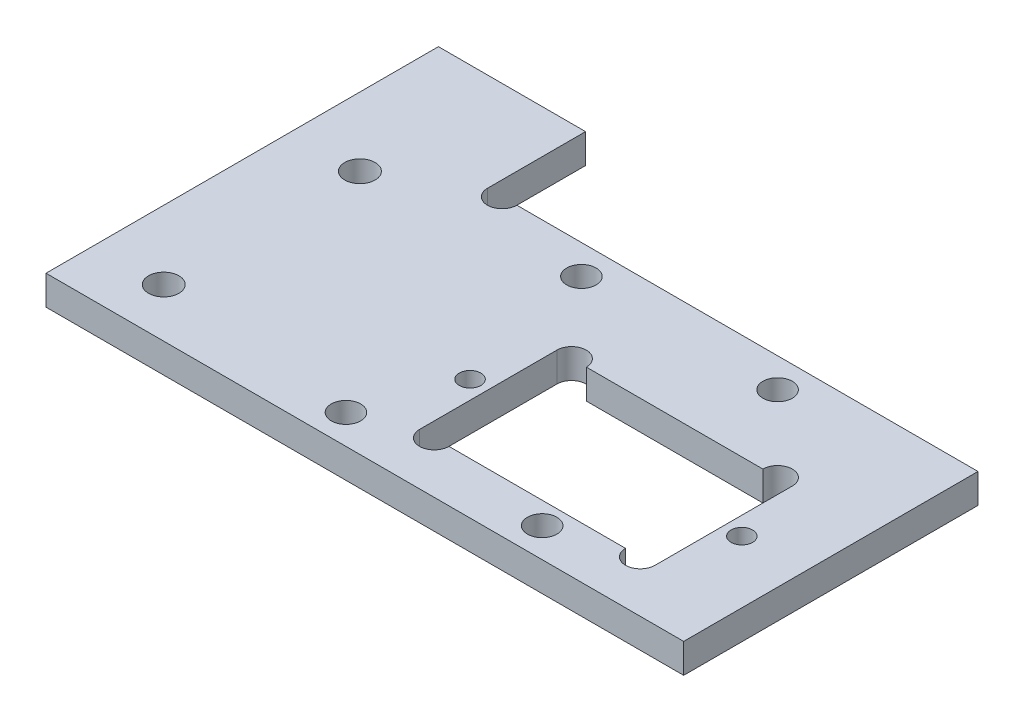
SolidWorks part; units mm, degrees
material "Thornel Mat VMA"
ref_plane "前视基准面" through (0, 0, 0) normal (0, 0, 1) x (1, 0, 0)
ref_plane "上视基准面" through (0, 0, 0) normal (0, 1, 0) x (1, 0, 0)
ref_plane "右视基准面" through (0, 0, 0) normal (1, 0, 0) x (0, 0, -1)
sketch "草图1" plane through (0, 0, 0) normal (0, 1, 0) x (1, 0, 0)
  line L0 (0, 20) -> (0, -20) construction
  line L1 (-32.5, 20) -> (32.5, 20)
  line L2 (-32.5, 20) -> (-32.5, -20)
  line L3 (-32.5, -20) -> (32.5, -20)
  line L4 (32.5, 20) -> (32.5, -20)
  line L5 (-32.5, 20) -> (32.5, -20) construction
  line L6 (-32.5, -20) -> (32.5, 20) construction
  point P0 (0, 0)
  dimension "D1" = 40
  dimension "D2" = 65
extrude "凸台-拉伸1" add sketch "草图1" along normal blind 3
ref_plane "基准面1" through (0, 0, 0) normal (0, -1, 0) x (-1, 0, 0)
ref_plane "基准面2" through (0, 0, 0) normal (0, -1, 0) x (-1, 0, 0)
sketch "草图2" plane through (0, 0, 0) normal (0, -1, 0) x (-1, 0, 0)
  line L0 (25.5, -20) -> (25.5, -15) construction
  line L1 (32.5, -20) -> (-32.5, -20) construction
  line L2 (25.5, -15) -> (25.5, 5) construction
  line L3 (32.5, 20) -> (32.5, -20) construction
  circle A0 centre (25.5, -15) radius 1.55
  circle A1 centre (25.5, 5) radius 1.55
  dimension "D1" = 3.1
  dimension "D2" = 3.1
  dimension "D3" = 7
  dimension "D4" = 5
  dimension "D5" = 20
extrude "切除-拉伸1" cut sketch "草图2" against normal blind 10
sketch "草图3" plane through (0, 0, 0) normal (0, -1, 0) x (-1, 0, 0)
  line L1 (-32.5, 20) -> (17.5, 20)
  line L2 (-32.5, 20) -> (-32.5, 10)
  line L3 (-32.5, 10) -> (17.5, 10)
  line L4 (17.5, 20) -> (17.5, 10)
  dimension "D1" = 10
  dimension "D2" = 50
extrude "切除-拉伸2" cut sketch "草图3" against normal blind 10
ref_plane "基准面3" through (0, 0, 0) normal (0, -1, 0) x (-1, 0, 0)
sketch "草图4" plane through (0, 0, 0) normal (0, -1, 0) x (-1, 0, 0)
  line L0 (-23.8249, -1.5) -> (-0.8249, -14) construction
  line L2 (-24.3249, -0.75) -> (-0.3249, -0.75)
  line L3 (-24.3249, -0.75) -> (-24.3249, -14.75)
  line L4 (-24.3249, -14.75) -> (-0.3249, -14.75)
  line L5 (-0.3249, -0.75) -> (-0.3249, -14.75)
  line L6 (-24.3249, -0.75) -> (-0.3249, -14.75) construction
  line L7 (-24.3249, -14.75) -> (-0.3249, -0.75) construction
  point P4 (-12.3249, -7.75)
  dimension "D1" = 24
  dimension "D2" = 14
extrude "切除-拉伸3" cut sketch "草图4" against normal blind 10
ref_plane "基准面4" through (0, 3, 0) normal (0, 1, 0) x (1, 0, 0)
sketch "草图5" plane through (0, 3, 0) normal (0, 1, 0) x (1, 0, 0)
  circle A0 centre (26.1749, -7.75) radius 1.1
  circle A1 centre (-1.5251, -7.75) radius 1.1
  dimension "D1" = 2.2
  dimension "D2" = 2.2
extrude "切除-拉伸4" cut sketch "草图5" against normal blind 10
sketch "草图6" plane through (0, 0, 0) normal (0, -1, 0) x (-1, 0, 0)
  circle A0 centre (-15.075, -17) radius 1.5
  circle A1 centre (4.925, -17) radius 1.5
  circle A2 centre (-15.075, 7) radius 1.5
  circle A3 centre (4.925, 7) radius 1.5
extrude "切除-拉伸5" cut sketch "草图6" against normal blind 25
sketch "草图7" plane through (0, 3, 0) normal (0, 1, 0) x (1, 0, 0)
  line L0 (0.3249, -0.75) -> (1.8249, -0.75)
  line L1 (24.3249, -0.75) -> (0.3249, -0.75) construction
  line L2 (24.3249, -0.75) -> (22.8249, -0.75)
  line L3 (0.3249, -14.75) -> (1.8249, -14.75)
  line L4 (0.3249, -14.75) -> (24.3249, -14.75) construction
  line L5 (24.3249, -14.75) -> (22.8249, -14.75)
  line L6 (-17.5, 10) -> (-16, 10)
  line L7 (-17.5, 10) -> (32.5, 10) construction
  dimension "D1" = 1.5
  dimension "D2" = 1.5
  dimension "D3" = 1.5
  dimension "D4" = 1.5
  dimension "D5" = 1.5
sketch "草图8" plane through (0, 3, 0) normal (0, 1, 0) x (1, 0, 0)
  point P0 (-16, 10)
  point P3 (1.8249, -0.75)
  point P6 (22.8249, -0.75)
  point P9 (22.8249, -14.75)
  point P12 (1.8249, -14.75)
hole_wizard "孔1" positions "草图8" profile "草图9" legacy end condition up to next
sketch "草图9" plane through (-16, 3, -10) normal (1, 0, 0) x (0, 0, 1)
  line L0 (0, 0) -> (0, 3)
  line L1 (0, 3) -> (1.5, 3)
  line L2 (1.5, 3) -> (1.5, 0)
  line L3 (1.5, 0) -> (0, 0)
  line L4 (0, 110) -> (0, -10) construction
  dimension "直径" = 3
  dimension "深度" = 3
